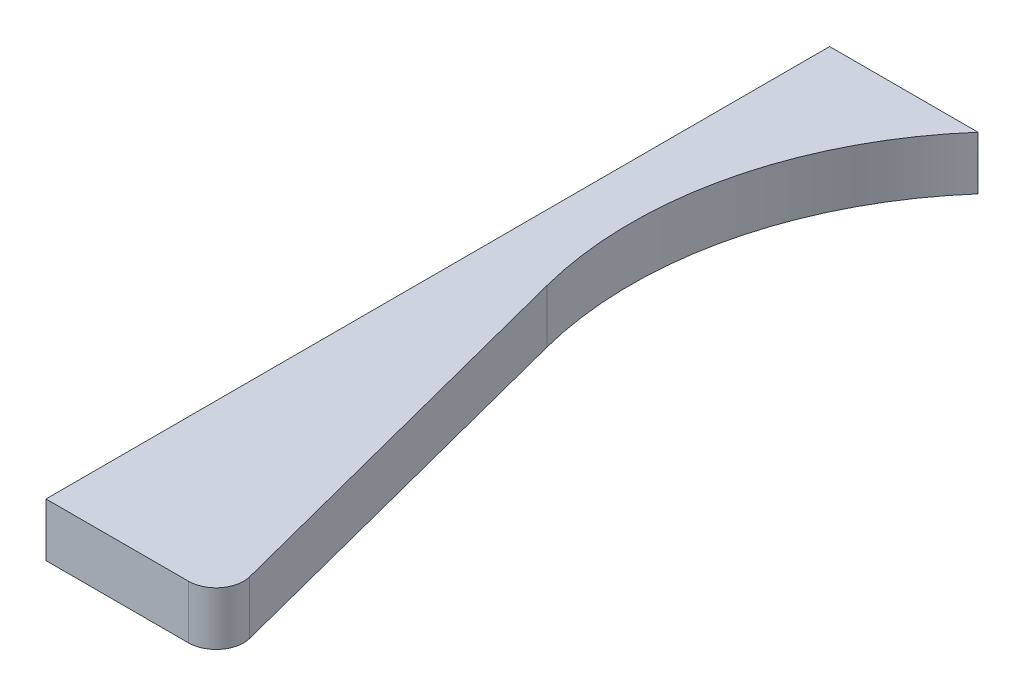
SolidWorks part; units mm, degrees
material "Pine"
ref_plane "Front Plane" through (0, 0, 0) normal (0, 0, 1) x (1, 0, 0)
ref_plane "Top Plane" through (0, 0, 0) normal (0, 1, 0) x (1, 0, 0)
ref_plane "Right Plane" through (0, 0, 0) normal (1, 0, 0) x (0, 0, -1)
sketch "Sketch1" plane through (0, 0, 0) normal (0, 1, 0) x (1, 0, 0)
  line L26 (50.8, -279.4) -> (0, -279.4)
  line L27 (0, -279.4) -> (0, 0)
  line L29 (60.3296, -267.0954) -> (23.3895, -124.12)
  line L30 (52.9071, 0) -> (0, 0)
  line L32 (19.05, -89.9772) -> (0, -89.9772) construction
  arc A31 (50.8, -279.4) -> (60.3296, -267.0954) centre (50.8, -269.5575) ccw
  arc A37 (23.3895, -124.12) -> (52.9071, 0) centre (155.5382, -89.9772) cw
  point P2 (0, 58.2656)
  dimension "D5" = 136.4882
  dimension "D2" = 50.8
  dimension "D4" = 9.8425
  dimension "D6" = 279.4
  dimension "D3" = 19.05
  dimension "D1" = 89.9772
extrude "Boss-Extrude1" add sketch "Sketch1" along normal blind 19.05
